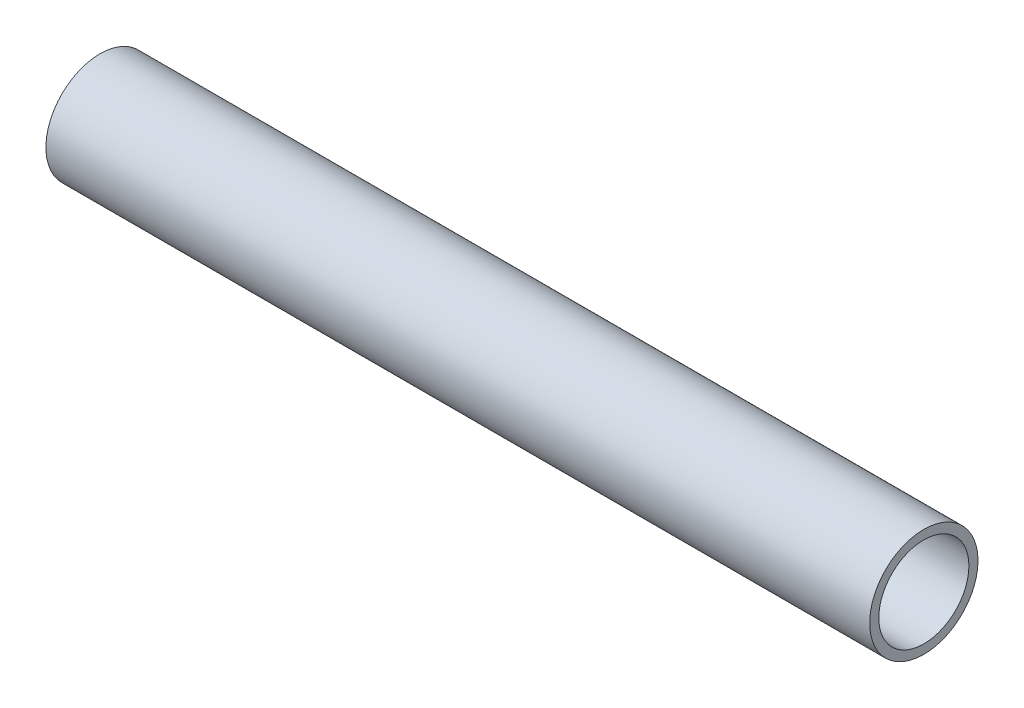
SolidWorks part; units mm, degrees
ref_plane "Front Plane" through (0, 0, 0) normal (0, 0, 1) x (1, 0, 0)
ref_plane "Top Plane" through (0, 0, 0) normal (0, 1, 0) x (1, 0, 0)
ref_plane "Right Plane" through (0, 0, 0) normal (1, 0, 0) x (0, 0, -1)
sketch "Sketch1" plane through (0, 0, 0) normal (0, 0, 1) x (1, 0, 0)
  line L0 (-135.3503, 1471.8597) -> (-38.7684, 1471.8597)
  point P2 (0, 0)
  point P3 (-116.1126, 1477.6528)
  point P4 (-114.9684, 1471.8549)
  point P5 (29.7464, 1471.6737)
  point P7 (30.5688, 1471.6409)
  point P8 (31.6036, 1471.8597)
  point P9 (-136.005, 1471.7932)
  point P10 (-136.005, 1471.7932)
  point P12 (-38.7684, 1471.8597)
  point P13 (-135.3503, 1471.8597)
other "Pipe 0.5 SCH 40(1)"
ref_plane "Plane1" through (-135.3503, 1471.8597, 0) normal (1, 0, 0) x (0, 1, 0)
sketch "Sketch11" plane through (-135.3503, 1471.8597, 0) normal (1, 0, 0) x (0, 1, 0)
  circle A0 centre (0, 0) radius 5.2832
  circle A1 centre (0, 0) radius 6.35
  point P5 (0, 0)
  dimension "D1" = 12.7
  dimension "D2" = 10.5664
